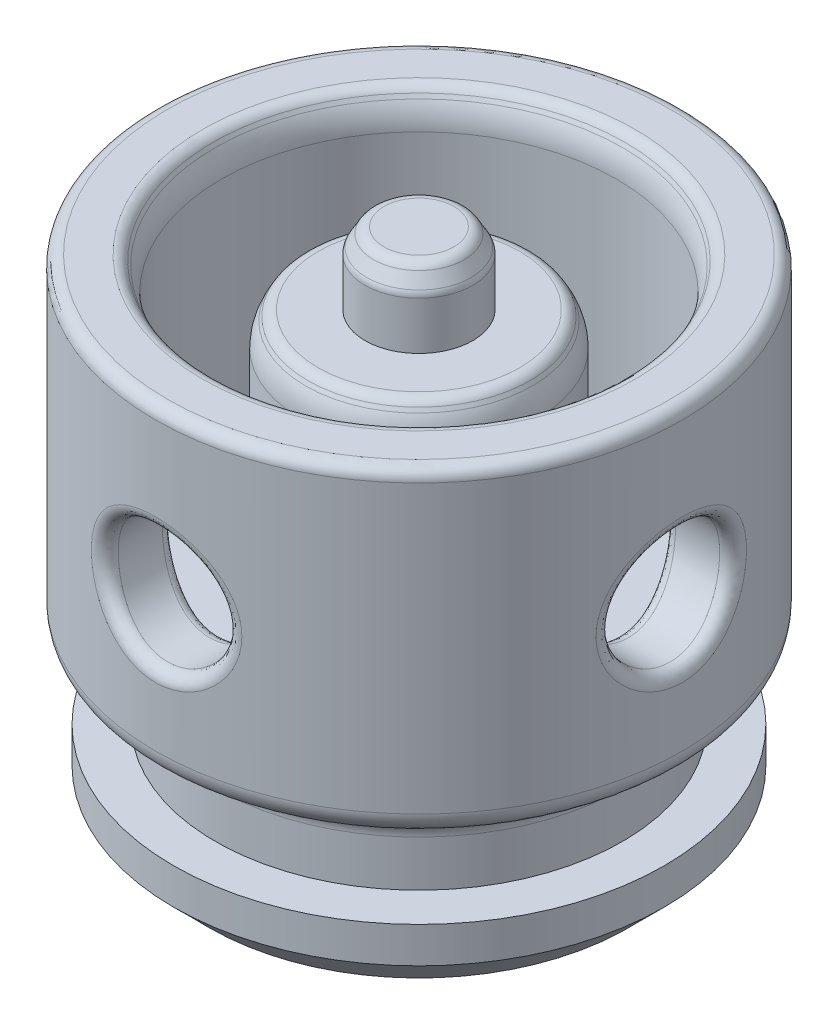
SolidWorks part; units mm, degrees
ref_plane "Ebene vorne" through (0, 0, 0) normal (0, 0, 1) x (1, 0, 0)
ref_plane "Ebene oben" through (0, 0, 0) normal (0, 1, 0) x (1, 0, 0)
ref_plane "Ebene rechts" through (0, 0, 0) normal (1, 0, 0) x (0, 0, -1)
sketch "Skizze1" plane through (0, 0, 0) normal (0, 0, 1) x (1, 0, 0)
  line L0 (0, 0) -> (0, 18) construction
  line L1 (0, 18) -> (5, 18)
  line L2 (5, 18) -> (5, 8)
  line L3 (5, 8) -> (8.25, 8)
  line L4 (8.25, 8) -> (8.25, 20)
  line L5 (8.25, 20) -> (11, 20)
  line L6 (11, 20) -> (11, 6.9434)
  line L7 (10.25, 0) -> (10.25, 3)
  line L8 (10.25, 3) -> (8.5, 3)
  line L9 (10.25, 0) -> (0, 0)
  line L10 (8.5, 3) -> (8.5, 5.5)
  line L11 (8.5, 5.5) -> (11, 6.9434)
  line L12 (0, 0) -> (0, 18)
  dimension "D1" = 10
  dimension "D2" = 16.5
  dimension "D3" = 22
  dimension "D4" = 10
  dimension "D5" = 12
  dimension "D6" = 17
  dimension "D7" = 1.75
  dimension "D8" = 3
  dimension "D9" = 60
  dimension "D10" = 2.5
  dimension "D11" = 8
revolve "Rotation1" add sketch "Skizze1" angle 360 about L0
chamfer "Fase1" distance 1.5 angle 45 1 edges at (0, 0, -10.25)
ref_plane "Ebene1" through (11, 0, 0) normal (1, 0, 0) x (0, 0, -1)
sketch "Skizze4" plane through (11, 0, 0) normal (1, 0, 0) x (0, 0, -1)
  line L0 (0, 20) -> (0, 8) construction
  line L1 (8.25, 20) -> (-8.25, 20) construction
  line L2 (8.25, 8) -> (-8.25, 8) construction
  circle A0 centre (0, 13) radius 2.5
  dimension "D2" = 5
  dimension "D1" = 5
extrude "Schnitt-Linear austragen2" cut sketch "Skizze4" against normal up to next
pattern_circular "Kreismuster1" count 2 over 90 about axis through (0, 0, 0) along (0, -1, 0) of "Schnitt-Linear austragen2"
chamfer "Fase2" distance 0.5 angle 60 2 edges at (0, 18, -5) (0, 20, -8.25)
fillet "Verrundung4" radius 2 2 edges at (0, 17.134, 5) (0, 19.134, 8.25)
fillet "Verrundung5" radius 1 2 edges at (0, 6.9434, -11) (0, 5.5, -8.5)
fillet "Verrundung6" radius 0.5 3 edges at (0, 18, 4.5) (0, 20, -11) (0, 20, 8.75)
sketch "Skizze3" plane through (0, 18, 0) normal (0, 1, 0) x (1, 0, 0)
  circle A0 centre (0, 0) radius 2.25
  dimension "D1" = 4.5
extrude "Aufsatz-Linear austragen1" add sketch "Skizze3" along normal blind 3
chamfer "Fase3" distance 0.5 angle 60 1 edges at (0, 21, 2.25)
fillet "Verrundung7" radius 0.5 2 edges at (0, 21, 1.75) (0, 20.134, 2.25)
fillet "Verrundung8" radius 0.5 4 edges at (-2.4487, 13.504, 10.724) (-2.4589, 12.5484, 7.8751) (10.724, 13.504, 2.4487) (7.8751, 12.5484, 2.4589)
